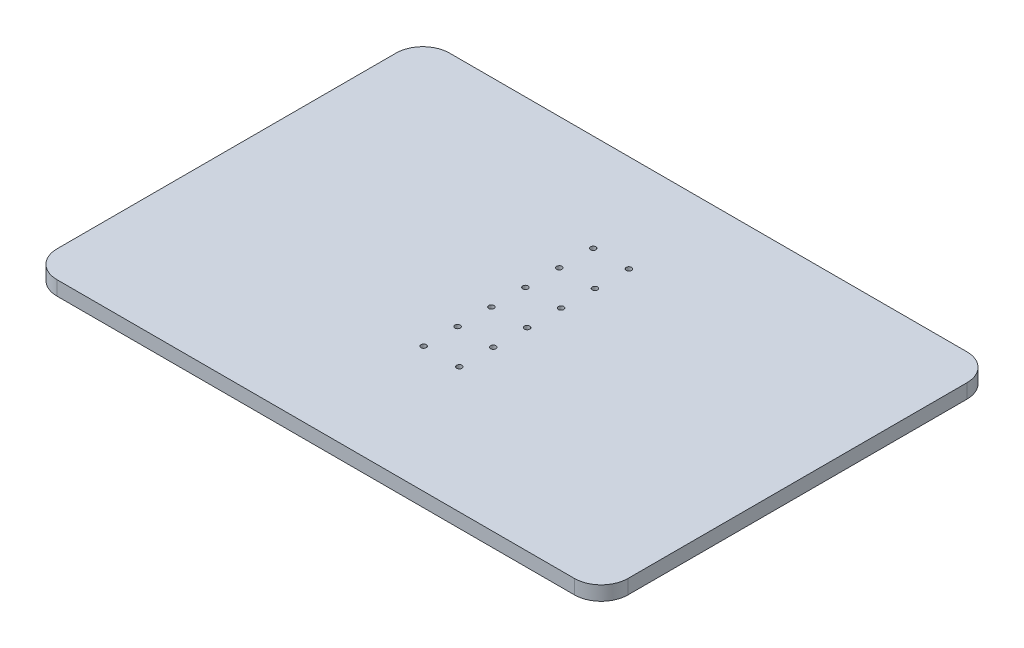
SolidWorks part; units mm, degrees
ref_plane "Front" through (0, 0, 0) normal (0, 0, 1) x (1, 0, 0)
ref_plane "Top" through (0, 0, 0) normal (0, 1, 0) x (1, 0, 0)
ref_plane "Right" through (0, 0, 0) normal (1, 0, 0) x (0, 0, -1)
sketch "Sketch1" plane through (0, 0, 0) normal (0, 1, 0) x (1, 0, 0)
  line L1 (160, 110) -> (-160, 110)
  line L2 (160, 110) -> (160, -110)
  line L3 (160, -110) -> (-160, -110)
  line L4 (-160, 110) -> (-160, -110)
  line L5 (160, 110) -> (-160, -110) construction
  line L6 (160, -110) -> (-160, 110) construction
  point P0 (0, 0)
  dimension "D1" = 320
  dimension "D2" = 220
extrude "Boss-Extrude1" add sketch "Sketch1" along normal blind 8
fillet "Fillet1" radius 15 4 edges at (-160, 4, -110) (-160, 4, 110) (160, 4, 110) (160, 4, -110)
sketch "Sketch3" plane through (0, 8, 0) normal (0, 1, 0) x (1, 0, 0)
  line L0 (0, 0) -> (0, -110) construction
  line L2 (0, 0) -> (-160, 0) construction
  line L3 (-160, 95) -> (-160, -95) construction
  line L4 (-10, -1.5) -> (-10, -110) construction
  line L5 (-145, -110) -> (145, -110) construction
  line L11 (-145, -110) -> (145, -110) construction
  circle A0 centre (-10, -1.5) radius 1.5
  dimension "D1" = 3
  dimension "D2" = 10
extrude "Cut-Extrude2" cut sketch "Sketch3" against normal up to next
pattern_linear "LPattern2" count 4 spacing 19 along (0, 0, -1) count 3 spacing 19 along (0, 0, 1) of "Cut-Extrude2"
mirror "Mirror2" about plane through (0, 0, 0) normal (1, 0, 0) of "LPattern2", "Cut-Extrude2"
